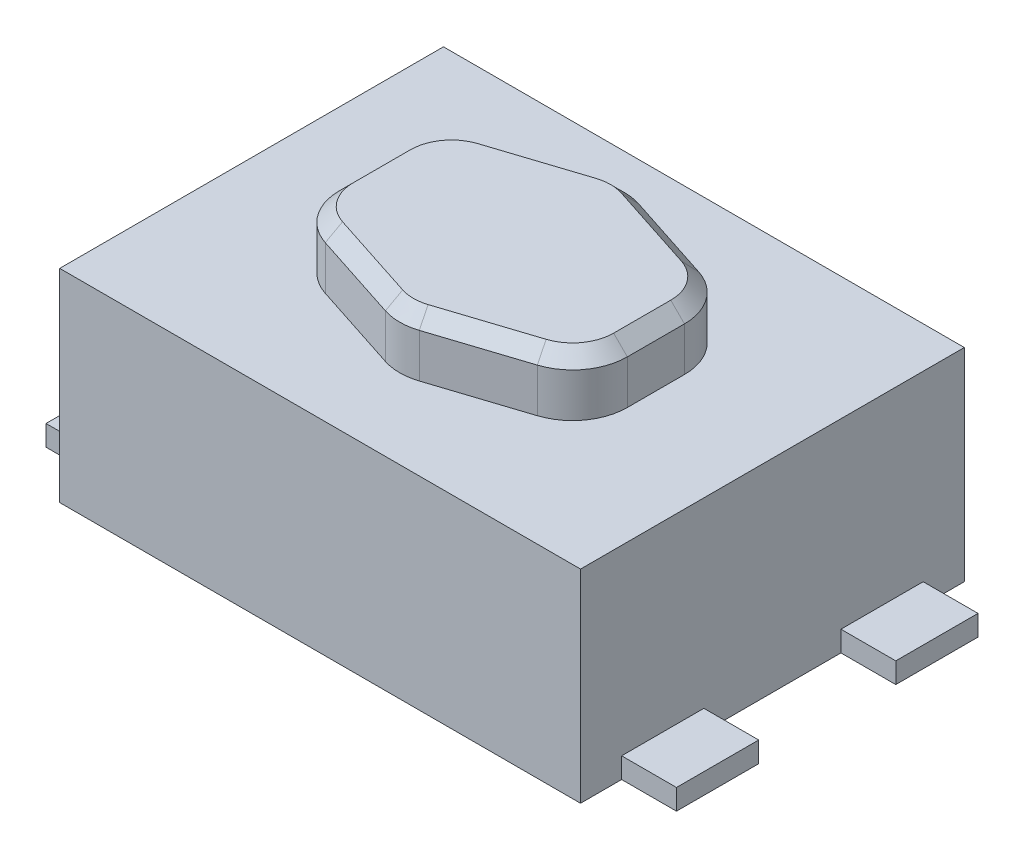
SolidWorks part; units mm, degrees
ref_plane "Plan de face" through (0, 0, 0) normal (0, 0, 1) x (1, 0, 0)
ref_plane "Plan de dessus" through (0, 0, 0) normal (0, 1, 0) x (1, 0, 0)
ref_plane "Plan de droite" through (0, 0, 0) normal (1, 0, 0) x (0, 0, -1)
sketch "Esquisse2" plane through (0, 0, 0) normal (0, 1, 0) x (1, 0, 0)
  line L1 (-1.9, -1.4) -> (1.9, -1.4)
  line L2 (-1.9, -1.4) -> (-1.9, 1.4)
  line L3 (-1.9, 1.4) -> (1.9, 1.4)
  line L4 (1.9, -1.4) -> (1.9, 1.4)
  line L5 (-1.9, -1.4) -> (1.9, 1.4) construction
  line L6 (-1.9, 1.4) -> (1.9, -1.4) construction
  point P0 (0, 0)
  dimension "D1" = 2.8
  dimension "D2" = 3.8
extrude "Boss.-Extru.1" add sketch "Esquisse2" along normal blind 1.48
sketch "Esquisse3" plane through (0, 0, 0) normal (0, 1, 0) x (1, 0, 0)
  line L0 (0.1236, -0.8) -> (0.1236, 0.8) construction
  line L1 (0.1236, 0.8) -> (0.7736, 0.5888)
  line L2 (1.05, 0.2084) -> (1.05, -0.2084)
  line L3 (0.7736, -0.5888) -> (0.1236, -0.8)
  line L4 (1.05, 0) -> (0.1236, 0) construction
  line L5 (0.1236, 0) -> (0, 0) construction
  line L6 (0, -0.8196) -> (0, 0.8196) construction
  line L7 (0, 0.8196) -> (-0.1615, 0.8196) construction
  line L8 (-1.05, 0.2084) -> (-1.05, -0.2084)
  line L9 (-0.1236, 0.8) -> (-0.7736, 0.5888)
  line L10 (-0.7736, -0.5888) -> (-0.1236, -0.8)
  arc A0 (0.7736, 0.5888) -> (1.05, 0.2084) centre (0.65, 0.2084) cw
  arc A1 (1.05, -0.2084) -> (0.7736, -0.5888) centre (0.65, -0.2084) cw
  arc A2 (0.1236, 0.8) -> (-0.1236, 0.8) centre (0, 0.4196) ccw
  arc A3 (0.1236, -0.8) -> (-0.1236, -0.8) centre (0, -0.4196) cw
  arc A4 (-0.7736, 0.5888) -> (-1.05, 0.2084) centre (-0.65, 0.2084) ccw
  arc A5 (-1.05, -0.2084) -> (-0.7736, -0.5888) centre (-0.65, -0.2084) ccw
  dimension "D4" = 0.4
  dimension "D1" = 1.05
  dimension "D2" = 1.6
  dimension "D3" = 18
extrude "Boss.-Extru.2" add sketch "Esquisse3" along normal blind 1.9
chamfer "Chanfrein1" distance 0.1 angle 45 12 edges at (0.4486, 1.9, -0.6944) (0.9736, 1.9, -0.4435) (1.05, 1.9, 0) (0.9736, 1.9, 0.4435) (0.4486, 1.9, 0.6944) (0, 1.9, 0.8196) (-0.4486, 1.9, 0.6944) (-0.9736, 1.9, 0.4435) (-1.05, 1.9, 0) (-0.9736, 1.9, -0.4435) (-0.4486, 1.9, -0.6944) (0, 1.9, -0.8196)
sketch "Esquisse4" plane through (0, 0, 0) normal (0, 1, 0) x (1, 0, 0)
  line L0 (-1.9, 1.4) -> (-1.9, -1.4) construction
  line L1 (-1.9, 1.1) -> (-2.3, 1.1)
  line L2 (-1.9, 1.1) -> (-1.9, 0.5)
  line L3 (-1.9, 0.5) -> (-2.3, 0.5)
  line L4 (-2.3, 1.1) -> (-2.3, 0.5)
  line L5 (1.9, -1.4) -> (1.9, 1.4) construction
  line L6 (-1.9, -0.5) -> (-2.3, -0.5)
  line L7 (-1.9, -0.5) -> (-1.9, -1.1)
  line L8 (-1.9, -1.1) -> (-2.3, -1.1)
  line L9 (-2.3, -0.5) -> (-2.3, -1.1)
  line L10 (1.9, -0.5) -> (2.3, -0.5)
  line L11 (1.9, -0.5) -> (1.9, -1.1)
  line L12 (1.9, -1.1) -> (2.3, -1.1)
  line L13 (2.3, -0.5) -> (2.3, -1.1)
  line L14 (-2.3, 0.5) -> (-2.3, -0.5) construction
  line L15 (1.9, 0.5) -> (2.3, 0.5)
  line L16 (1.9, 0.5) -> (1.9, 1.1)
  line L17 (1.9, 1.1) -> (2.3, 1.1)
  line L18 (2.3, 0.5) -> (2.3, 1.1)
  line L19 (-2.3, 0) -> (0, 0) construction
  dimension "D1" = 0.6
  dimension "D2" = 4.6
  dimension "D3" = 2.2
extrude "Boss.-Extru.3" add sketch "Esquisse4" along normal blind 0.15
